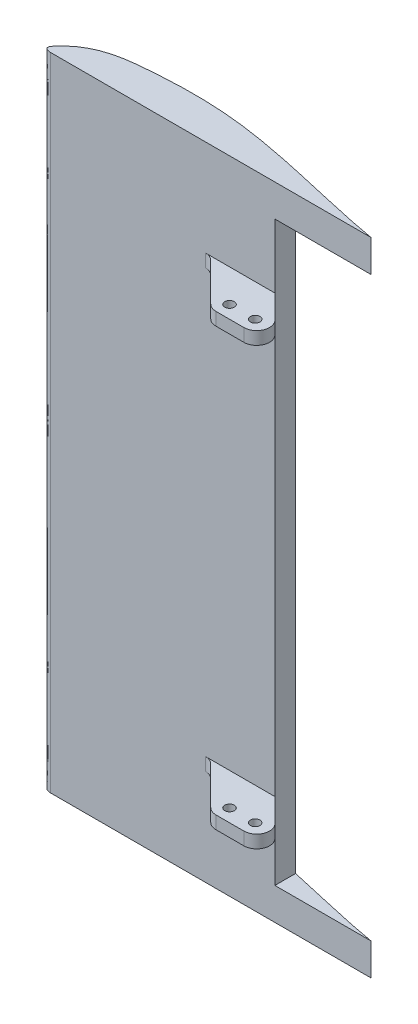
SolidWorks part; units mm, degrees
ref_plane "Front Plane" through (0, 0, 0) normal (0, 0, 1) x (1, 0, 0)
ref_plane "Top Plane" through (0, 0, 0) normal (0, 1, 0) x (1, 0, 0)
ref_plane "Right Plane" through (0, 0, 0) normal (1, 0, 0) x (0, 0, -1)
sketch "Sketch1" plane through (0, 0, 0) normal (0, 1, 0) x (1, 0, 0)
  line L0 (-23.8352, 0) -> (26.1648, 0)
  spline S0 degree 3 poles (-24.2676, 1.2562) (-22.2782, 3.5536) (-18.7384, 4.7933) (-8.8501, 5.7749) (4.1327, 5.525) (19.2119, 1.1626) (26.1648, 0) knots 0.021997 0.021997 0.021997 0.021997 0.155271 0.206186 0.531145 1 1 1 1
  spline S1 degree 2 poles (-24.2676, 1.2562) (-25.3671, 0.1243) (-23.8352, 0) knots 0 0 0 1 1 1
  dimension "D1" = 50
extrude "Boss-Extrude1" add sketch "Sketch1" along normal blind 100
ref_plane "Plane1" through (0, 0, 10) normal (0, 0, 1) x (1, 0, 0)
sketch "Sketch2" plane through (0, 0, 10) normal (0, 0, 1) x (1, 0, 0)
  line L0 (26.1648, 100) -> (26.1648, 0) construction
  line L1 (26.1648, 95) -> (11.1648, 95)
  line L2 (26.1648, 95) -> (26.1648, 5)
  line L3 (26.1648, 5) -> (11.1648, 5)
  line L4 (11.1648, 95) -> (11.1648, 5)
  line L5 (-23.8352, 100) -> (26.1648, 100) construction
  line L6 (-23.8352, 0) -> (26.1648, 0) construction
  dimension "D1" = 15
  dimension "D2" = 5
  dimension "D3" = 5
extrude "Cut-Extrude3" cut sketch "Sketch2" against normal blind 100
sketch "Sketch3" plane through (0, 0, 0) normal (0, 0, 1) x (1, 0, 0)
  line L0 (11.1648, 5) -> (11.1648, 95) construction
  line L1 (11.1648, 85) -> (1.1648, 85)
  line L2 (11.1648, 85) -> (11.1648, 83)
  line L3 (11.1648, 83) -> (1.1648, 83)
  line L4 (1.1648, 85) -> (1.1648, 83)
  line L5 (11.1648, 95) -> (26.1648, 95) construction
  line L6 (11.1648, 15) -> (1.1648, 15)
  line L7 (11.1648, 15) -> (11.1648, 17)
  line L8 (11.1648, 17) -> (1.1648, 17)
  line L9 (1.1648, 15) -> (1.1648, 17)
  line L10 (26.1648, 5) -> (11.1648, 5) construction
  dimension "D1" = 10
  dimension "D2" = 2
  dimension "D3" = 10
  dimension "D4" = 2
  dimension "D5" = 10
  dimension "D6" = 10
sketch "Sketch4" plane through (0, 0, 0) normal (0, -1, 0) x (1, 0, 0)
  line L0 (3.1365, 0) -> (-0.0276, -3.1641)
  line L1 (-23.8352, 0) -> (26.1648, 0) construction
  dimension "D1" = 45
extrude "Boss-Extrude2" add sketch "Sketch3" along direction (-0.7071, 0, -0.7071) on the side of the normal blind 10 contours L4 L3 L2 L1 | L6 L9 L8 L7
fillet "Fillet1" radius 2 4 edges at (18.2359, 84, 7.0711) (8.2359, 84, 7.0711) (18.2359, 16, 7.0711) (8.2359, 16, 7.0711)
fillet "Fillet2" radius 2 2 edges at (1.1648, 84, 0) (1.1648, 16, 0)
sketch "Sketch5" plane through (0, 85, 0) normal (0, 1, 0) x (1, 0, 0)
  line L0 (13.4075, -7.0711) -> (9.0643, -7.0711) construction
  circle A0 centre (9.1648, -5.0711) radius 0.75
  circle A1 centre (13.1648, -5.0711) radius 0.75
  dimension "D1" = 1.5
  dimension "D2" = 2
  dimension "D3" = 2
  dimension "D4" = 1.5
  dimension "D5" = 2
  dimension "D6" = 2
extrude "Cut-Extrude4" cut sketch "Sketch5" against normal blind 110
